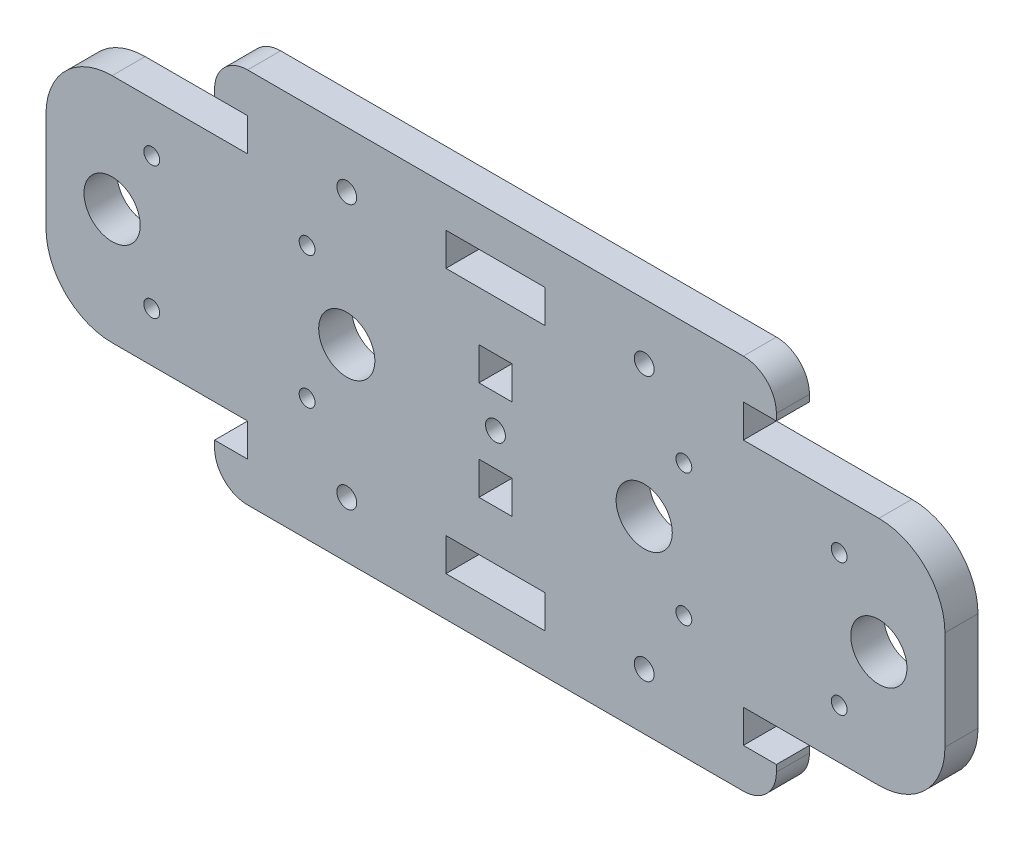
SolidWorks part; units mm, degrees
ref_plane "Plan de face" through (0, 0, 0) normal (0, 0, 1) x (1, 0, 0)
ref_plane "Plan de dessus" through (0, 0, 0) normal (0, 1, 0) x (1, 0, 0)
ref_plane "Plan de droite" through (0, 0, 0) normal (1, 0, 0) x (0, 0, -1)
sketch "Esquisse1" plane through (0, 0, 0) normal (0, 0, 1) x (1, 0, 0)
  line L0 (-20, 0) -> (20, 0)
  line L1 (20, 0) -> (20, 6)
  line L2 (20, 6) -> (15, 6)
  line L3 (15, 6) -> (15, 11)
  line L4 (15, 11) -> (20, 11)
  line L5 (20, 11) -> (20, 46) construction
  line L6 (20, 46) -> (15, 46)
  line L7 (15, 46) -> (15, 51)
  line L8 (15, 51) -> (20, 51)
  line L9 (20, 51) -> (20, 57)
  line L10 (20, 57) -> (-20, 57)
  line L11 (-20, 57) -> (-20, 51) construction
  line L12 (-20, 51) -> (-15, 51)
  line L13 (-15, 51) -> (-15, 46)
  line L14 (-15, 46) -> (-20, 46)
  line L15 (-20, 46) -> (-20, 11) construction
  line L16 (-20, 11) -> (-15, 11)
  line L17 (-15, 11) -> (-15, 6)
  line L18 (-15, 6) -> (-20, 6)
  line L19 (-20, 6) -> (-20, 0) construction
  line L20 (0, 0) -> (0, 57) construction
  line L21 (-15, 8.5) -> (15, 8.5) construction
  line L22 (15, 48.5) -> (-15, 48.5) construction
  line L23 (-20, 28.5) -> (20, 28.5) construction
  line L24 (-22.5, 57) -> (-22.5, 0) construction
  line L25 (-30, 46) -> (-25, 46)
  line L26 (-30, 51) -> (-30, 46)
  line L27 (-25, 51) -> (-30, 51)
  line L28 (-25, 57) -> (-25, 51) construction
  line L29 (-65, 57) -> (-25, 57)
  line L30 (-65, 51) -> (-65, 57)
  line L31 (-60, 51) -> (-65, 51)
  line L32 (-60, 46) -> (-60, 51)
  line L33 (-65, 46) -> (-60, 46)
  line L34 (-65, 11) -> (-65, 46) construction
  line L35 (-60, 11) -> (-65, 11)
  line L36 (-60, 6) -> (-60, 11)
  line L37 (-65, 6) -> (-60, 6)
  line L38 (-65, 0) -> (-65, 6)
  line L39 (-25, 0) -> (-65, 0)
  line L40 (-25, 6) -> (-25, 0) construction
  line L41 (-30, 6) -> (-25, 6)
  line L42 (-30, 11) -> (-30, 6)
  line L43 (-25, 11) -> (-30, 11)
  line L44 (-25, 51) -> (-20, 51)
  line L45 (-20, 46) -> (-25, 46)
  line L46 (-25, 11) -> (-20, 11)
  line L47 (-20, 6) -> (-25, 6)
  line L48 (-25, 57) -> (-20, 57)
  line L49 (-20, 0) -> (-25, 0)
  line L50 (20, 46) -> (45.5, 46)
  line L51 (45.5, 46) -> (45.5, 11)
  line L52 (45.5, 11) -> (20, 11)
  line L53 (45.5, 28.5) -> (20, 28.5) construction
  line L54 (-90.5, 11) -> (-65, 11)
  line L55 (-90.5, 46) -> (-90.5, 11)
  line L56 (-65, 46) -> (-90.5, 46)
  line L57 (29.5, 38.5) -> (29.5, 18.5) construction
  line L58 (35.5, 28.5) -> (35.5, 40.3355) construction
  circle A0 centre (0, 48.5) radius 1.5
  circle A1 centre (0, 8.5) radius 1.5
  circle A2 centre (0, 28.5) radius 4.25
  circle A3 centre (-20, 28.5) radius 1.6 construction
  circle A4 centre (20, 28.5) radius 1.6 construction
  circle A5 centre (-45, 8.5) radius 1.5
  circle A6 centre (-45, 28.5) radius 4.25
  circle A7 centre (-45, 48.5) radius 1.5
  circle A8 centre (6, 38.5) radius 1.2
  circle A9 centre (6, 18.5) radius 1.2
  circle A10 centre (-51, 18.5) radius 1.2
  circle A11 centre (-51, 38.5) radius 1.2
  circle A12 centre (35.5, 28.5) radius 4.25
  circle A13 centre (-80.5, 28.5) radius 4.25
  circle A14 centre (29.5, 38.5) radius 1.2
  circle A15 centre (29.5, 18.5) radius 1.2
  circle A16 centre (-74.5, 18.5) radius 1.2
  circle A17 centre (-74.5, 38.5) radius 1.2
  circle A18 centre (35.5, 28.5) radius 5.5025 construction
  line B0 (-22.5, 23.5) -> (-22.5, 33.5) construction
  line B1 (-25, 23.5) -> (-25, 18.5)
  line B2 (-25, 23.5) -> (-20, 23.5)
  line B3 (-20, 23.5) -> (-20, 18.5)
  line B4 (-25, 18.5) -> (-20, 18.5)
  line B5 (-25, 33.5) -> (-25, 38.5)
  line B6 (-25, 33.5) -> (-20, 33.5)
  line B7 (-20, 33.5) -> (-20, 38.5)
  line B8 (-25, 38.5) -> (-20, 38.5)
  circle B9 centre (-22.5, 28.5) radius 1.5
  dimension "D6" = 3
  dimension "D7" = 3
  dimension "D8" = 8.5
  dimension "D10" = 3.2
  dimension "D12" = 5
  dimension "D15" = 2.4
  dimension "D16" = 68
  dimension "D20" = 11.0051
  dimension "D1" = 5
  dimension "D2" = 30
  dimension "D3" = 40
  dimension "D4" = 6
  dimension "D5" = 40
  dimension "D9" = 40
  dimension "D11" = 20
  dimension "D13" = 20
  dimension "D14" = 6
  dimension "D17" = 58
  dimension "D18" = 6
  dimension "D19" = 20
sketch_block_instance "Trou M3 plots 5mm-55"
sketch_block "Trou M3 plots 5mm" parameters "D2"=3, "D1"=5, "D3"=5, "D4"=8
extrude "Boss.-Extru.1" add sketch "Esquisse1" along normal blind 5
fillet "Congé1" radius 5 4 edges at (20, 57, 2.5) (20, 0, 2.5) (-65, 0, 2.5) (-65, 57, 2.5)
fillet "Congé2" radius 10 4 edges at (-90.5, 11, 2.5) (-90.5, 46, 2.5) (45.5, 11, 2.5) (45.5, 46, 2.5)
